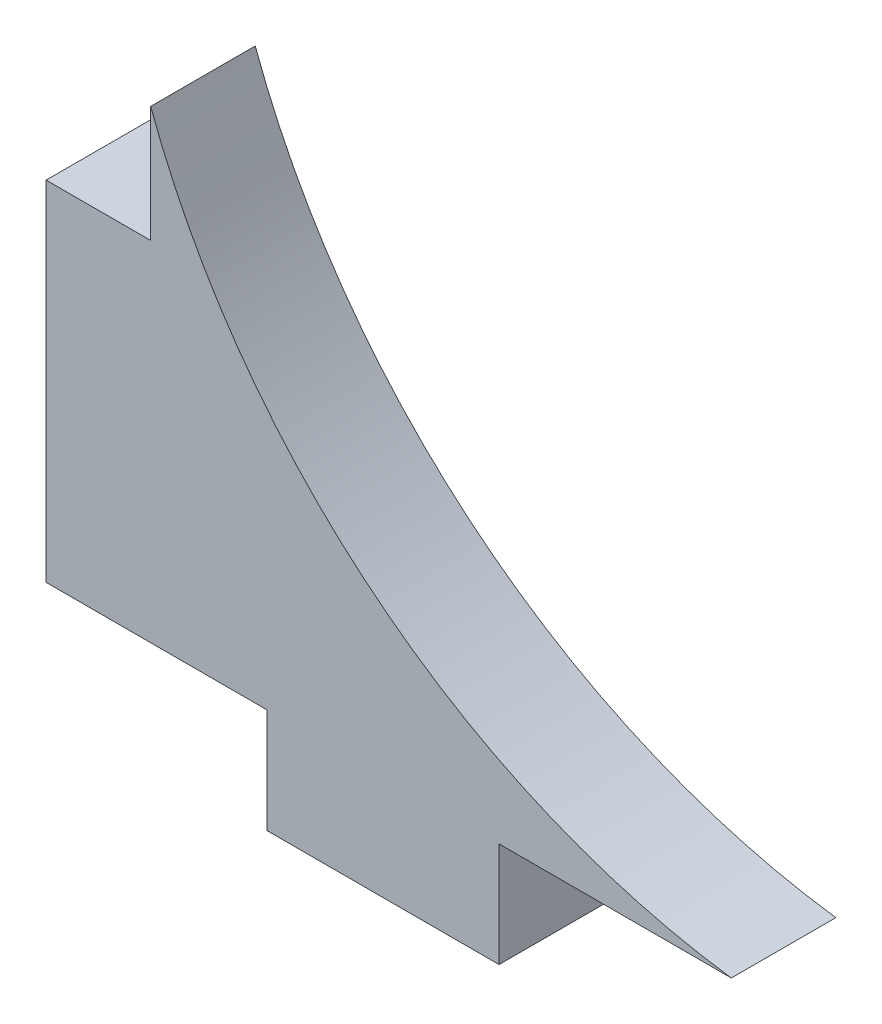
SolidWorks part; units mm, degrees
ref_plane "Front Plane" through (0, 0, 0) normal (0, 0, 1) x (1, 0, 0)
ref_plane "Top Plane" through (0, 0, 0) normal (0, 1, 0) x (1, 0, 0)
ref_plane "Right Plane" through (0, 0, 0) normal (1, 0, 0) x (0, 0, -1)
sketch "Model" plane through (0, 0, 0) normal (0, 0, 1) x (1, 0, 0)
  line L0 (-10, 9) -> (-29, 9)
  line L2 (-10, 9) -> (-10, 0)
  line L3 (-10, 0) -> (10, 0)
  line L4 (10, 9) -> (10, 0)
  line L5 (30, 9) -> (10, 9)
  line L8 (-29, 9) -> (-29, 39)
  line L11 (-29, 39) -> (-20, 39)
  line L12 (-20, 49) -> (-20, 39)
  arc A0 (-20, 49) -> (30, 9) centre (38.2844, 70.6055) ccw
  dimension "D4" = 9
  dimension "D6" = 20
  dimension "D10" = 9
  dimension "D16" = 19
  dimension "D2" = 30
  dimension "D3" = 20
  dimension "D5" = 10
  dimension "D7" = 61.6055
extrude "Boss-Extrude1" add sketch "Model" along normal blind 9
equation "\"tab-width-small\" = 20mm ' Width of the small version of the Tab"
equation "\"material-thickness\" = 9mm"
equation "\"D4@Model\" = \"material-thickness\""
equation "\"D10@Model\" = \"material-thickness\""
equation "\"D1@Boss-Extrude1\"= \"material-thickness\""
equation "\"D16@Model\"=\"material-thickness\"+10"
equation "\"D6@Model\"=\"tab-width-small\""
